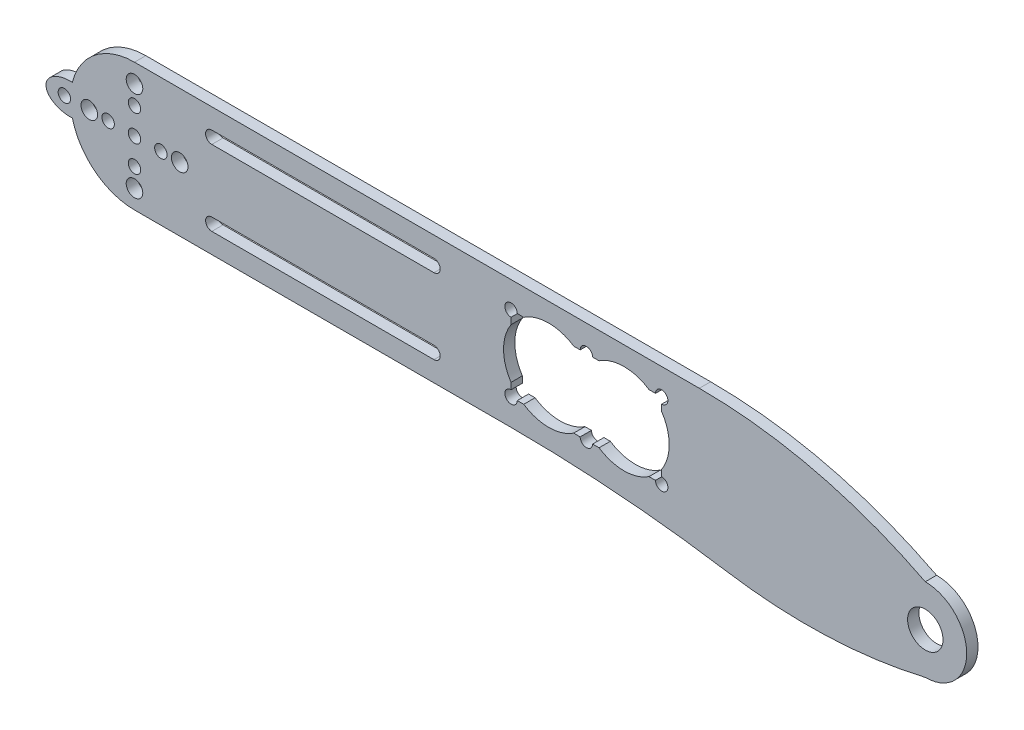
SolidWorks part; units mm, degrees
ref_plane "前视基准面" through (0, 0, 0) normal (0, 0, 1) x (1, 0, 0)
ref_plane "上视基准面" through (0, 0, 0) normal (0, 1, 0) x (1, 0, 0)
ref_plane "右视基准面" through (0, 0, 0) normal (1, 0, 0) x (0, 0, -1)
sketch "草图1" plane through (0, 0, 0) normal (0, 0, 1) x (1, 0, 0)
  line L0 (0, 17) -> (150, 17)
  line L1 (0, 0) -> (150, 0)
  line L2 (0, 0) -> (0, 34)
  line L3 (0, 34) -> (150, 34)
  line L4 (210, 8.5) -> (210, 19.5)
  line L5 (100, 27) -> (100, 7)
  line L6 (140, 7) -> (140, 27)
  line L7 (210, 8.5) -> (220.0394, 8.5)
  line L8 (100, 27) -> (140, 27)
  line L9 (100, 7) -> (140, 7)
  line L11 (0, 17) -> (-17, 17)
  line L13 (-20.2513, 17) -> (-17, 17)
  line L19 (150, 0) -> (230, 0)
  line L20 (150, 17) -> (230, 17)
  line L24 (210, 17) -> (210, 0)
  line L25 (210, 17) -> (220, 17)
  line L26 (210, 0) -> (220, 0)
  line L27 (220, 17) -> (220, 0)
  line L30 (150, 34) -> (130.1532, 34)
  line L31 (150, 0) -> (130, 0)
  line L34 (100, 34) -> (100.849, 34)
  line L35 (210, 17) -> (207.9214, 17)
  line L36 (20.5317, 28.65) -> (79.5257, 28.65)
  line L40 (79.5257, 25.35) -> (20.5317, 25.35)
  line L41 (150, 34) -> (100, 34)
  line L42 (150, 0) -> (100, 0)
  line L44 (79.5257, 8.65) -> (20.5317, 8.65)
  line L45 (20.5317, 5.35) -> (79.5257, 5.35)
  circle A0 centre (0, 17) radius 17
  circle A1 centre (0, 17) radius 7
  circle A2 centre (0, 24) radius 1.65
  circle A3 centre (7, 17) radius 1.65
  circle A4 centre (0, 10) radius 1.65
  circle A5 centre (-7, 17) radius 1.65
  circle A6 centre (-18.6257, 17) radius 1.65
  circle A7 centre (120, 27) radius 1.65
  circle A8 centre (120, 7) radius 1.65
  circle A9 centre (130, 17) radius 12
  circle A10 centre (110, 17) radius 12
  arc A12 (100, 34) -> (157.2349, 38.4778) centre (100, 402.029) ccw
  arc A13 (100, 0) -> (157.2349, -4.4778) centre (100, -368.0289) cw
  circle A14 centre (210, 8.5) radius 4.7
  circle A16 centre (162, 17) radius 22
  arc A17 (150, 34) -> (210, 19.5) centre (150, -97.3879) cw
  circle A18 centre (20.5317, 27) radius 1.65
  circle A19 centre (79.5257, 27) radius 1.65
  circle A20 centre (0, 17) radius 1.65
  circle A21 centre (100, 27) radius 1.65
  circle A22 centre (100, 7) radius 1.65
  circle A25 centre (140, 27) radius 1.65
  circle A26 centre (140, 7) radius 1.65
  circle A27 centre (79.5257, 7) radius 1.65
  circle A28 centre (20.5317, 7) radius 1.65
  arc A29 (157.2349, -4.4778) -> (210, -2.5) centre (178.574, 131.0665) ccw
  circle A30 centre (0, 29) radius 2.2
  circle A31 centre (0, 5) radius 2.2
  circle A32 centre (12, 17) radius 2.2
  circle A33 centre (-12, 17) radius 2.2
  circle A34 centre (210, 8.5) radius 11
  ellipse E0 centre (-17, 17) end of major axis (-23.5027, 17) minor radius 4.1193
extrude "凸台-拉伸2" add sketch "草图1" along normal blind 3
sketch "草图2" plane through (0, 0, 3) normal (0, 0, 1) x (1, 0, 0)
  circle A0 centre (210, 8.5) radius 5
  circle A1 centre (210, 8.5) radius 5.9813
extrude "凸台-拉伸3" add sketch "草图2" against normal blind 3
